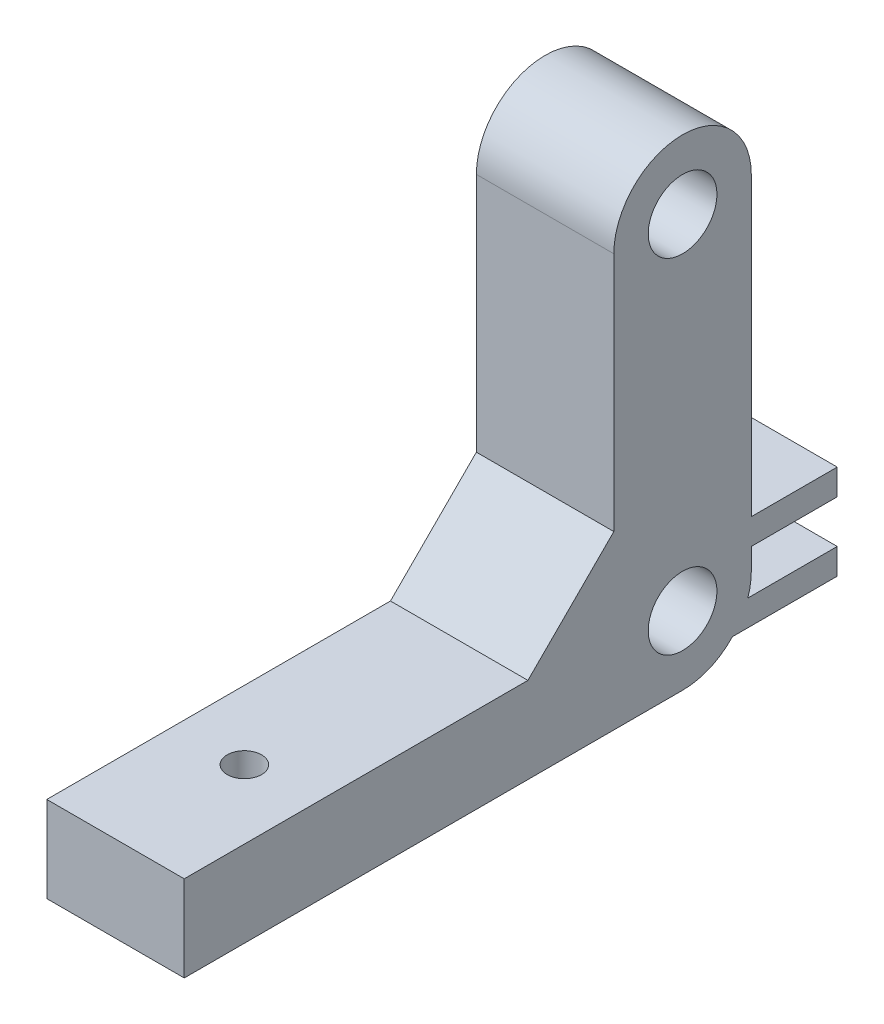
SolidWorks part; units mm, degrees
material "ABS"
ref_plane "Front Plane" through (0, 0, 0) normal (0, 0, 1) x (1, 0, 0)
ref_plane "Top Plane" through (0, 0, 0) normal (0, 1, 0) x (1, 0, 0)
ref_plane "Right Plane" through (0, 0, 0) normal (1, 0, 0) x (0, 0, -1)
sketch "Sketch1" plane through (0, 0, 0) normal (1, 0, 0) x (0, 0, -1)
  line L0 (-10.3091, -58.7899) -> (-58.9824, -58.7899)
  line L1 (7.0176, -45.2899) -> (17.0176, -45.2899)
  line L2 (-8.9824, -10.7899) -> (-8.9824, -38.7899)
  line L3 (-10.3091, -58.7899) -> (-0.9824, -58.7899)
  line L4 (7.0176, -10.7899) -> (7.0176, -45.2899)
  line L5 (-58.9824, -58.7899) -> (-58.9824, -48.7899)
  line L6 (-58.9824, -48.7899) -> (-18.9824, -48.7899)
  line L7 (-8.9824, -38.7899) -> (-18.9824, -48.7899)
  line L8 (17.0176, -45.2899) -> (17.0176, -48.2899)
  line L9 (17.0176, -48.2899) -> (7.0176, -48.2899)
  line L10 (4.8271, -56.2899) -> (17.0176, -56.2899)
  line L11 (17.0176, -56.2899) -> (17.0176, -53.2899)
  line L12 (17.0176, -53.2899) -> (6.617, -53.2899)
  line L13 (7.0176, -48.2899) -> (7.0176, -50.7899)
  circle A0 centre (-0.9824, -10.7899) radius 4
  circle A1 centre (-0.9824, -50.7899) radius 4
  arc A2 (-8.9824, -10.7899) -> (7.0176, -10.7899) centre (-0.9824, -10.7899) cw
  arc A3 (-0.9824, -58.7899) -> (4.8271, -56.2899) centre (-0.9824, -50.7899) ccw
  arc A4 (6.617, -53.2899) -> (7.0176, -50.7899) centre (-0.9824, -50.7899) ccw
  point P8 (-8.9824, -48.7899)
  dimension "D1" = 8
  dimension "D2" = 8
  dimension "D4" = 8
  dimension "D11" = 8
  dimension "D3" = 40
  dimension "D5" = 8
  dimension "D6" = 8
  dimension "D7" = 8
  dimension "D8" = 8
  dimension "D9" = 50
  dimension "D10" = 10
  dimension "D12" = 3
  dimension "D14" = 3
  dimension "D15" = 5
  dimension "D16" = 2.5
  dimension "D17" = 10
extrude "Boss-Extrude1" add sketch "Sketch1" against normal blind 16
sketch "Sketch2" plane through (0, -48.7899, 0) normal (0, 1, 0) x (1, 0, 0)
  line L0 (-16, -58.9824) -> (0, -58.9824) construction
  line L1 (0, -18.9824) -> (0, -58.9824) construction
  circle A0 centre (-8, -43.9824) radius 2
  dimension "D1" = 4
  dimension "D2" = 15
  dimension "D3" = 8
extrude "Cut-Extrude1" cut sketch "Sketch2" against normal through all
ref_point "Point1"
sketch "Sketch3" plane through (0, -45.2899, 0) normal (0, 1, 0) x (1, 0, 0)
  line L0 (-16, 17.0176) -> (0, 17.0176) construction
  line L1 (0, 17.0176) -> (0, 7.0176) construction
  circle A0 centre (-8, 12.0176) radius 1.5
  dimension "D1" = 3
  dimension "D2" = 5
  dimension "D3" = 8
extrude "Cut-Extrude2" cut sketch "Sketch3" against normal through all
equation "\"rod_diameter\"= 8"
equation "\"D1@Sketch1\" = \"rod_diameter\""
equation "\"D2@Sketch1\"=\"rod_diameter\""
equation "\"D5@Sketch1\"  = \"rod_radius\" + \"rod_hole_thickness\""
equation "\"D6@Sketch1\"  = \"rod_radius\" + \"rod_hole_thickness\""
equation "\"D7@Sketch1\"  = \"rod_radius\" + \"rod_hole_thickness\""
equation "\"rod_hole_thickness\"= 4"
equation "\"D8@Sketch1\"  = \"rod_radius\" + \"rod_hole_thickness\""
equation "\"D4@Sketch1\"  = \"rod_radius\" + \"rod_hole_thickness\""
equation "\"D11@Sketch1\" = \"rod_radius\" + \"rod_hole_thickness\""
equation "\"rod_radius\"= \"rod_diameter\" / 2"
equation "\"D1@Boss-Extrude1\"= \"rod_diameter\" + \"rod_hole_thickness\" * 2"
equation "\"D3@Sketch2\"=\"rod_radius\"+\"rod_hole_thickness\""
equation "\"platter_diameter\"= 320"
equation "\"platter_radius\"= \"platter_diameter\" / 2"
equation "\"extruder_mount_hole_spacing\"= 75"
equation "\"arm_rod_spacing\"= 40"
equation "\"D3@Sketch1\"=\"arm_rod_spacing\""
equation "\"D2@Sketch3\" = \"D17@Sketch1\" / 2"
equation "\"D3@Sketch3\"= \"D1@Boss-Extrude1\" / 2"
